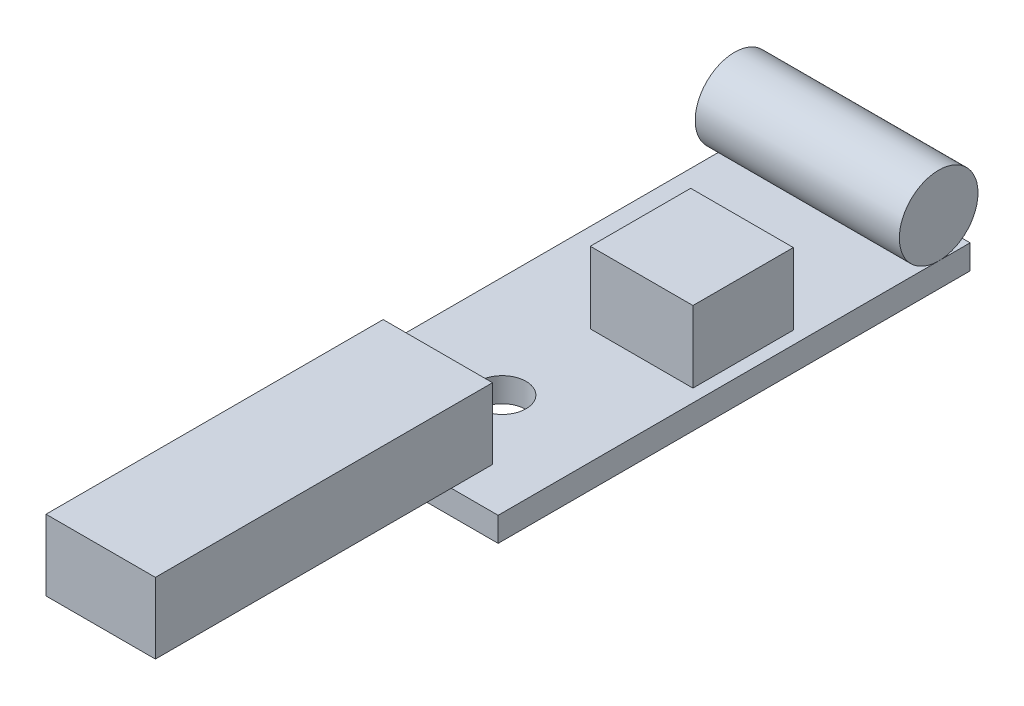
SolidWorks part; units mm, degrees
ref_plane "Front Plane" through (0, 0, 0) normal (0, 0, 1) x (1, 0, 0)
ref_plane "Top Plane" through (0, 0, 0) normal (0, 1, 0) x (1, 0, 0)
ref_plane "Right Plane" through (0, 0, 0) normal (1, 0, 0) x (0, 0, -1)
sketch "Sketch1" plane through (0, 0, 0) normal (0, 1, 0) x (1, 0, 0)
  line L1 (-6.9215, -16.002) -> (6.9215, -16.002)
  line L2 (-6.9215, -16.002) -> (-6.9215, 16.002)
  line L3 (-6.9215, 16.002) -> (6.9215, 16.002)
  line L4 (6.9215, -16.002) -> (6.9215, 16.002)
  line L5 (-6.9215, -16.002) -> (6.9215, 16.002) construction
  line L6 (-6.9215, 16.002) -> (6.9215, -16.002) construction
  circle A0 centre (0, -8.8011) radius 1.6129
  point P0 (0, 0)
  dimension "D3" = 3.2258
  dimension "D4" = 7.2009
  dimension "D1" = 13.843
  dimension "D2" = 32.004
extrude "Boss-Extrude1" add sketch "Sketch1" along normal blind 1.651
sketch "Sketch2" plane through (6.9215, 0, 0) normal (1, 0, 0) x (0, 0, -1)
  line L0 (-16.002, 1.651) -> (16.002, 1.651) construction
  line L1 (16.002, 1.651) -> (16.002, 0) construction
  circle A0 centre (13.8684, 4.318) radius 2.667
  dimension "D1" = 5.334
  dimension "D2" = 2.1336
extrude "Boss-Extrude2" add sketch "Sketch2" against normal up to surface (13.843 mm away) separate body up to face at (-6.9215, 0.8255, 0)
sketch "Sketch3" plane through (0, 1.651, 0) normal (0, 1, 0) x (1, 0, 0)
  line L1 (-0.9017, 4.8768) -> (6.0579, 4.8768)
  line L2 (-0.9017, 4.8768) -> (-0.9017, -1.9304)
  line L3 (-0.9017, -1.9304) -> (6.0579, -1.9304)
  line L4 (6.0579, 4.8768) -> (6.0579, -1.9304)
  line L5 (-0.9017, 4.8768) -> (6.0579, -1.9304) construction
  line L6 (-0.9017, -1.9304) -> (6.0579, 4.8768) construction
  line L7 (-6.9215, -16.002) -> (6.9215, -16.002) construction
  line L8 (6.9215, -16.002) -> (6.9215, 16.002) construction
  point P0 (2.5781, 1.4732)
  dimension "D1" = 0.8636
  dimension "D2" = 6.9596
  dimension "D3" = 6.8072
  dimension "D4" = 14.0716
extrude "Boss-Extrude3" add sketch "Sketch3" along normal blind 4.8514
sketch "Sketch4" plane through (0, 1.651, 0) normal (0, 1, 0) x (1, 0, 0)
  line L0 (6.9215, -16.002) -> (6.9215, 16.002) construction
  line L1 (-3.6703, -13.208) -> (3.7465, -13.208)
  line L2 (-3.6703, -13.208) -> (-3.6703, -36.068)
  line L3 (-3.6703, -36.068) -> (3.7465, -36.068)
  line L4 (3.7465, -13.208) -> (3.7465, -36.068)
  line L6 (-6.9215, -16.002) -> (6.9215, -16.002) construction
  dimension "D1" = 22.86
  dimension "D2" = 7.4168
  dimension "D3" = 3.175
  dimension "D4" = 2.794
extrude "Boss-Extrude4" add sketch "Sketch4" along normal blind 4.8006
